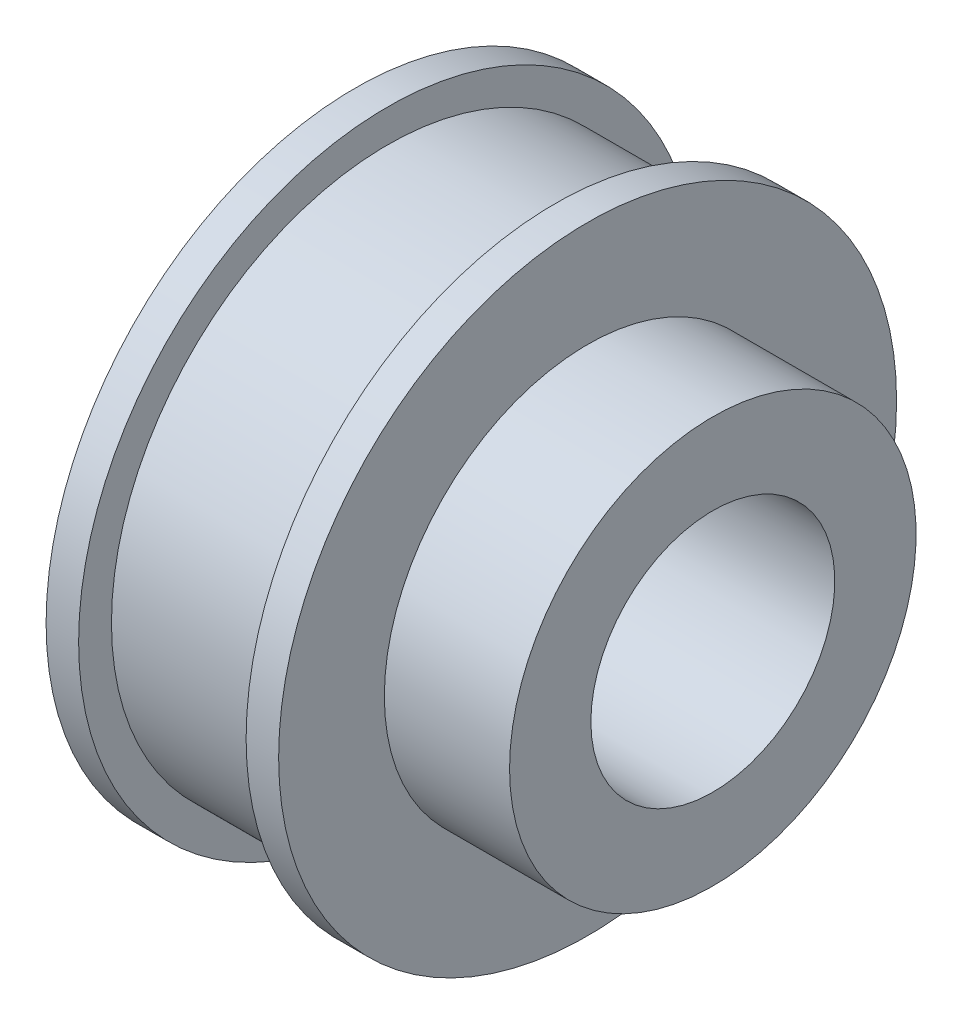
SolidWorks part; units mm, degrees
ref_plane "Plan de face" through (0, 0, 0) normal (0, 0, 1) x (1, 0, 0)
ref_plane "Plan de dessus" through (0, 0, 0) normal (0, 1, 0) x (1, 0, 0)
ref_plane "Plan de droite" through (0, 0, 0) normal (1, 0, 0) x (0, 0, -1)
sketch "Esquisse1" plane through (0, 0, 0) normal (0, 0, 1) x (1, 0, 0)
  line L0 (0, 0) -> (22, 0) construction
  line L1 (22, 7.5) -> (22, 12.5)
  line L2 (22, 12.5) -> (14.3, 12.5)
  line L3 (14.3, 12.5) -> (14.3, 19)
  line L4 (14.3, 19) -> (12.3, 19)
  line L5 (12.3, 19) -> (12.3, 16.98)
  line L6 (12.3, 16.98) -> (2, 16.98)
  line L7 (7.15, 16.98) -> (7.15, 32.1062) construction
  line L8 (0, 19) -> (2, 19)
  line L9 (2, 19) -> (2, 16.98)
  line L10 (0, 19) -> (0, 7.5)
  line L11 (0, 7.5) -> (22, 7.5)
  line L12 (0, 0) -> (0, 7.5) construction
  dimension "D1" = 14.3
  dimension "D2" = 2
  dimension "D3" = 38
  dimension "D4" = 33.96
  dimension "D5" = 22
  dimension "D6" = 25
  dimension "D7" = 15
revolve "Révolution1" add sketch "Esquisse1" angle 360 about L0
